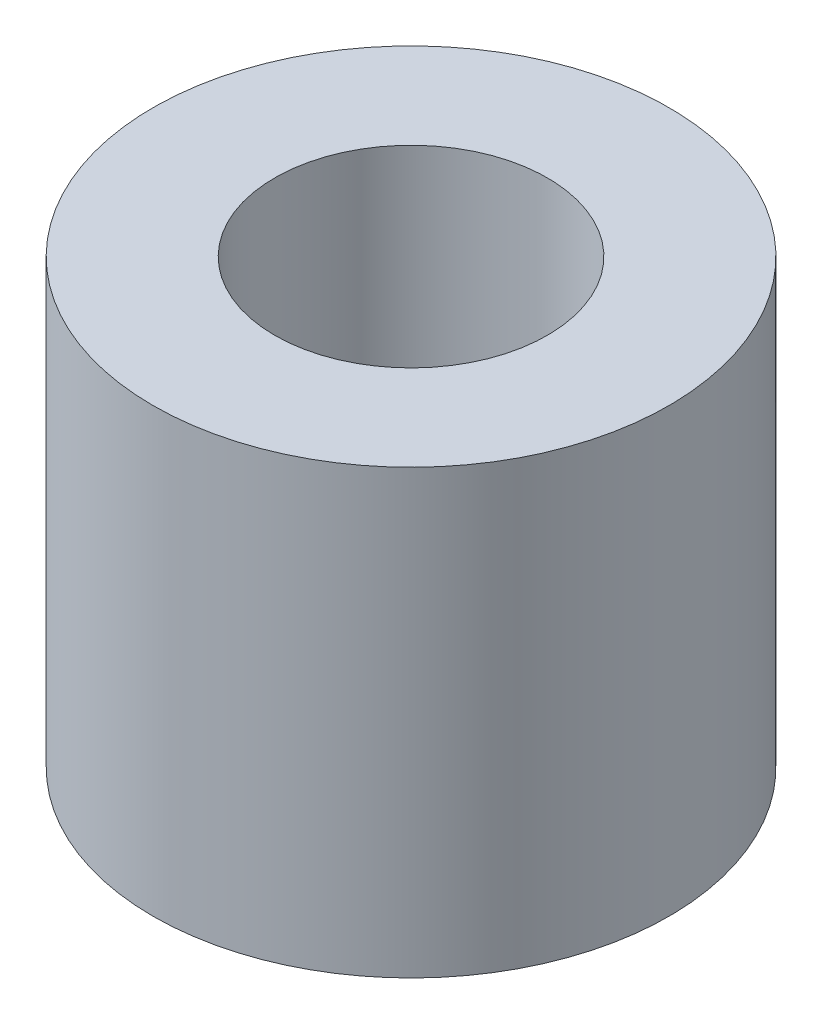
SolidWorks part; units mm, degrees
ref_plane "前视基准面" through (0, 0, 0) normal (0, 0, 1) x (1, 0, 0)
ref_plane "上视基准面" through (0, 0, 0) normal (0, 1, 0) x (1, 0, 0)
ref_plane "右视基准面" through (0, 0, 0) normal (1, 0, 0) x (0, 0, -1)
other "Configuration Table"
sketch "草图1" plane through (0, 0, 0) normal (0, 1, 0) x (1, 0, 0)
  circle A0 centre (0, 0) radius 1.85
  circle A1 centre (0, 0) radius 3.5
  dimension "D1" = 3.7
  dimension "D2" = 7
extrude "凸台-拉伸1" add sketch "草图1" along normal blind 6
